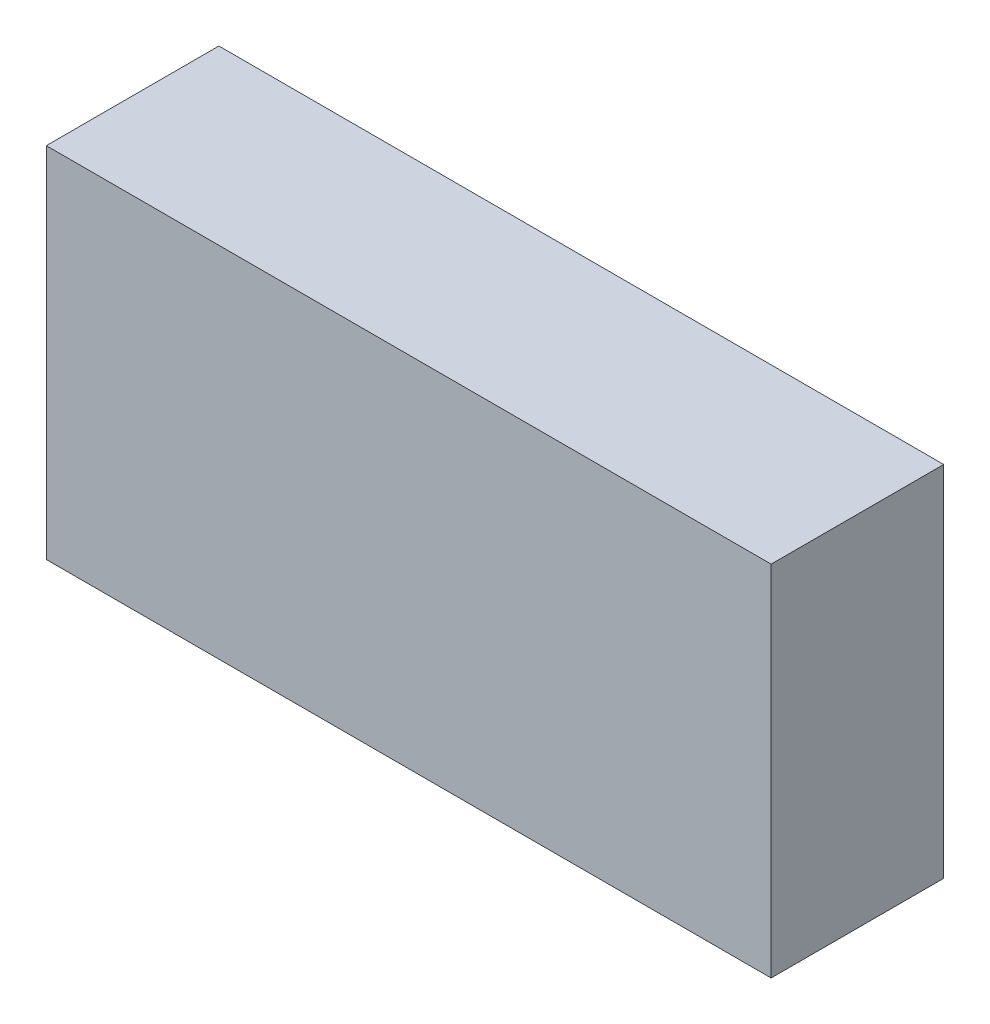
SolidWorks part; units mm, degrees
ref_plane "前视基准面" through (0, 0, 0) normal (0, 0, 1) x (1, 0, 0)
ref_plane "上视基准面" through (0, 0, 0) normal (0, 1, 0) x (1, 0, 0)
ref_plane "右视基准面" through (0, 0, 0) normal (1, 0, 0) x (0, 0, -1)
sketch "草图1" plane through (0, 0, 0) normal (0, 0, 1) x (1, 0, 0)
  line L0 (-1.365, 0.675) -> (-1.365, -0.675)
  line L1 (-1.365, -0.675) -> (1.365, -0.675)
  line L2 (1.365, -0.675) -> (1.365, 0.675)
  line L3 (1.365, 0.675) -> (-1.365, 0.675)
extrude "Component_Outline" add sketch "草图1" along normal blind 0.65 separate body
sketch3d "3D草图1"
  line L0 (0, 0, 0) -> (1, 0, 0)
  line L1 (0, 0, 0) -> (0, 1, 0)
  line L2 (0, 0, 0) -> (0, 0, 1)
  point P0 (0, 0, 0)
